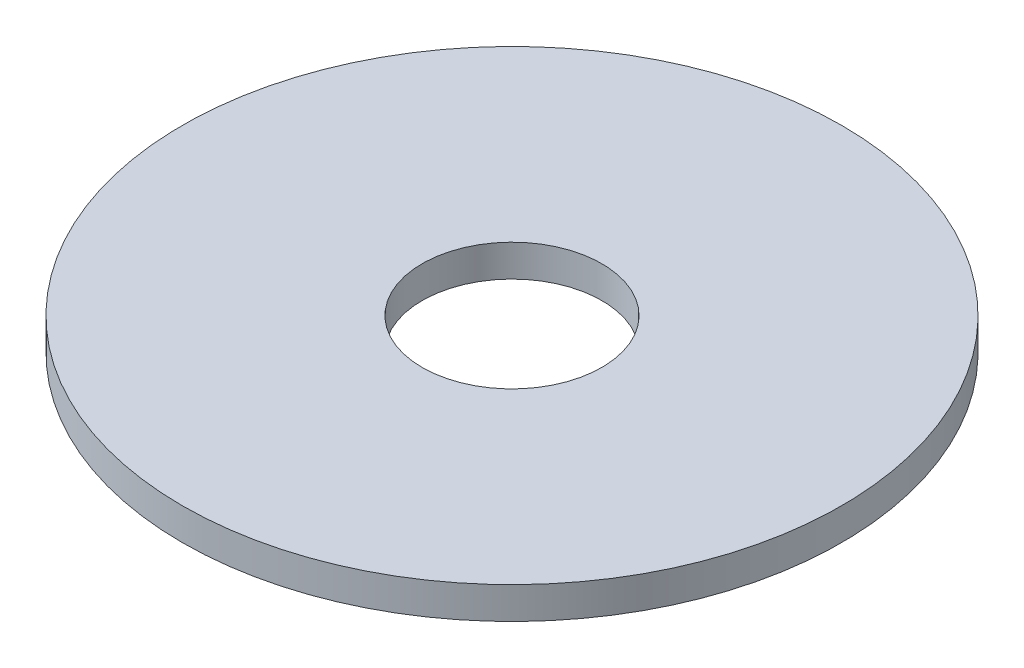
SolidWorks part; units mm, degrees
ref_plane "Front Plane" through (0, 0, 0) normal (0, 0, 1) x (1, 0, 0)
ref_plane "Top Plane" through (0, 0, 0) normal (0, 1, 0) x (1, 0, 0)
ref_plane "Right Plane" through (0, 0, 0) normal (1, 0, 0) x (0, 0, -1)
sketch "Sketch1" plane through (0, 0, 0) normal (0, 1, 0) x (1, 0, 0)
  circle A0 centre (0, 0) radius 8.25
extrude "Boss-Extrude1" add sketch "Sketch1" along normal blind 0.8
sketch "Sketch2" plane through (0, 0.8, 0) normal (0, 1, 0) x (1, 0, 0)
  line L0 (0, 0) -> (0, 0.25)
  circle A0 centre (0, 0) radius 2.25
extrude "Cut-Extrude1" cut sketch "Sketch2" against normal blind 5
